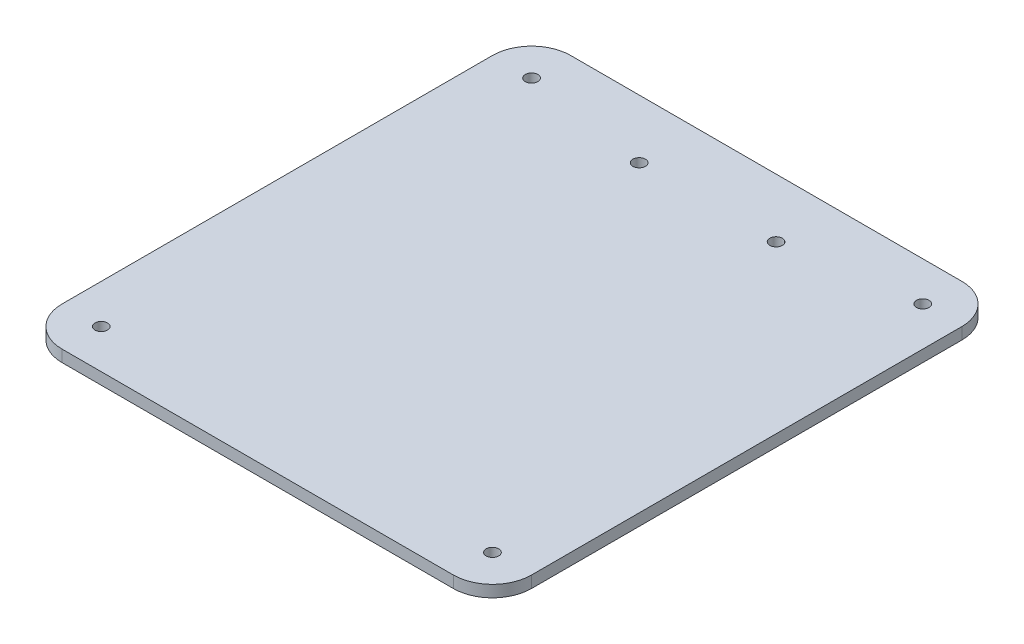
SolidWorks part; units mm, degrees
ref_plane "Front Plane" through (0, 0, 0) normal (0, 0, 1) x (1, 0, 0)
ref_plane "Top Plane" through (0, 0, 0) normal (0, 1, 0) x (1, 0, 0)
ref_plane "Right Plane" through (0, 0, 0) normal (1, 0, 0) x (0, 0, -1)
sketch "Sketch1" plane through (0, 0, 0) normal (0, 1, 0) x (1, 0, 0)
  line L0 (25.2381, 0) -> (225.0216, 0) construction
  line L1 (-50, 65) -> (50, 65)
  line L2 (-60, 55) -> (-60, -55)
  line L3 (-50, -65) -> (50, -65)
  line L4 (60, 55) -> (60, -55)
  line L5 (-60, 65) -> (60, -65) construction
  line L6 (-60, -65) -> (60, 65) construction
  line L7 (0, 0) -> (0, 90) construction
  arc A0 (-60, -55) -> (-50, -65) centre (-50, -55) ccw
  arc A1 (50, -65) -> (60, -55) centre (50, -55) ccw
  arc A2 (50, 65) -> (60, 55) centre (50, 55) cw
  arc A3 (-50, 65) -> (-60, 55) centre (-50, 55) ccw
  circle A6 centre (50, -55) radius 1.6
  circle A7 centre (-50, -55) radius 1.6
  circle A8 centre (50, 55) radius 1.6
  circle A9 centre (-50, 55) radius 1.6
  point P0 (0, 0)
extrude "Boss-Extrude1" add sketch "Sketch1" along normal blind 3
sketch "Sketch2" plane through (0, 3, 0) normal (0, 1, 0) x (1, 0, 0)
  line L0 (0, 10.0895) -> (0, 41.9666) construction
  circle A0 centre (-17.5, 50) radius 1.6
  circle A1 centre (17.5, 50) radius 1.6
  point P10 (-123.7481, 25.0402)
  dimension "D1" = 17.5
  dimension "D2" = 17.5
  dimension "D3" = 50
  dimension "D4" = 50
extrude "Cut-Extrude1" cut sketch "Sketch2" against normal through all
sketch "Sketch3" plane through (0, 3, 0) normal (0, 1, 0) x (1, 0, 0)
  line L0 (0, 0) -> (0, 26.7494) construction
  point P1 (0, 0)
  point P2 (0, 0)
